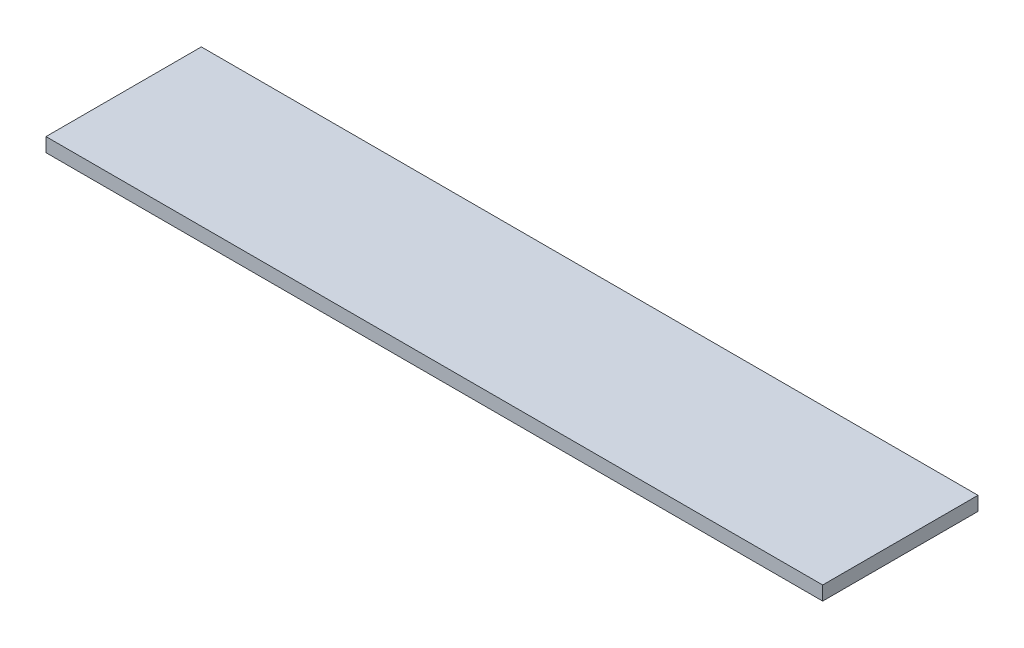
SolidWorks part; units mm, degrees
ref_plane "Front Plane" through (0, 0, 0) normal (0, 0, 1) x (1, 0, 0)
ref_plane "Top Plane" through (0, 0, 0) normal (0, 1, 0) x (1, 0, 0)
ref_plane "Right Plane" through (0, 0, 0) normal (1, 0, 0) x (0, 0, -1)
sketch "Esquisse1" plane through (0, 0, 0) normal (0, 1, 0) x (1, 0, 0)
  line L1 (-500, 100) -> (500, 100)
  line L2 (-500, 100) -> (-500, -100)
  line L3 (-500, -100) -> (500, -100)
  line L4 (500, 100) -> (500, -100)
  line L5 (-500, 100) -> (500, -100) construction
  line L6 (-500, -100) -> (500, 100) construction
  point P0 (0, 0)
extrude "Boss.-Extru.1" add sketch "Esquisse1" along normal blind 18
